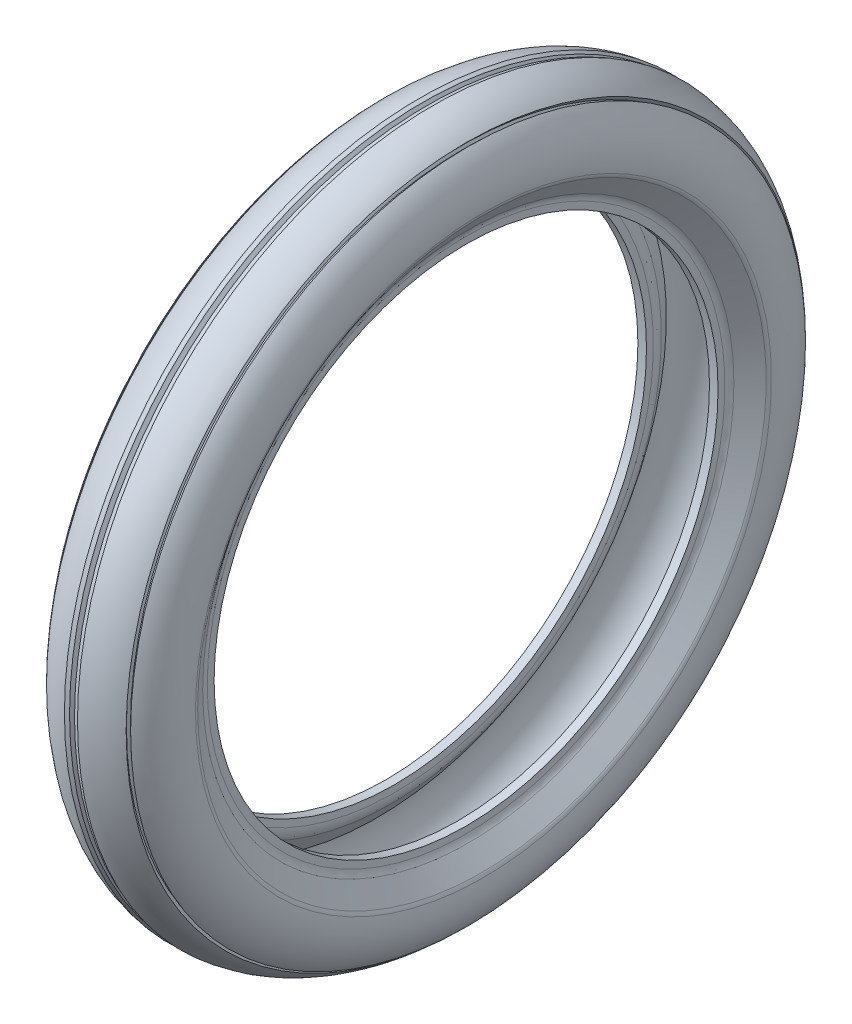
SolidWorks part; units mm, degrees
ref_plane "Front Plane" through (0, 0, 0) normal (0, 0, 1) x (1, 0, 0)
ref_plane "Top Plane" through (0, 0, 0) normal (0, 1, 0) x (1, 0, 0)
ref_plane "Right Plane" through (0, 0, 0) normal (1, 0, 0) x (0, 0, -1)
sketch "Sketch2" plane through (0, 0, 0) normal (0, 0, 1) x (1, 0, 0)
  line L0 (-71.6084, 0) -> (87.6813, 0) construction
  line L1 (0, 0) -> (0, 259.5059) construction
  line L2 (-35, 220) -> (-35, 226)
  line L3 (-36.9226, 231.8953) -> (-48.8214, 248.1984)
  line L4 (35, 220) -> (35, 226)
  line L5 (36.9226, 231.8953) -> (48.8214, 248.1984)
  line L6 (-27.5, 220) -> (-27.5, 226)
  line L7 (-30.8645, 236.3168) -> (-42.7633, 252.6199)
  line L8 (30.8645, 236.3168) -> (42.7633, 252.6199)
  line L9 (27.5, 220) -> (27.5, 226)
  line L10 (-27.5, 220) -> (-35, 220)
  line L11 (35, 220) -> (27.5, 220)
  line L12 (0, 343.7781) -> (0, 259.5059) construction
  line L16 (-5.6942, 310) -> (-2.6761, 308.5392)
  line L17 (-36.7306, 294.6191) -> (-32.5279, 290.6015)
  line L19 (-34.7713, 296.5603) -> (-31.3368, 292.9266)
  line L20 (34.7713, 296.5603) -> (31.3368, 292.9266)
  line L22 (36.7306, 294.6191) -> (32.5279, 290.6015)
  line L23 (-2.6761, 308.5392) -> (0, 304.4705)
  line L24 (0, 304.4705) -> (1.6662, 308.5392)
  line L25 (1.6662, 308.5392) -> (5.6942, 310)
  line L26 (-31.3368, 292.9266) -> (-32.5279, 290.6015)
  line L27 (32.5279, 290.6015) -> (31.3368, 292.9266)
  arc A0 (-50.1679, 251.4276) -> (-36.7306, 294.6191) centre (0, 259.5059) cw
  arc A1 (50.1679, 251.4276) -> (48.8214, 248.1984) centre (42.7633, 252.6199) cw
  arc A2 (-50.1679, 251.4276) -> (-48.8214, 248.1984) centre (-42.7633, 252.6199) ccw
  arc A3 (36.9226, 231.8953) -> (35, 226) centre (45, 226) ccw
  arc A4 (-36.9226, 231.8953) -> (-35, 226) centre (-45, 226) cw
  arc A5 (-30.8645, 236.3168) -> (-27.5, 226) centre (-45, 226) cw
  arc A6 (-42.7633, 252.6199) -> (-42.7633, 252.6199) centre (-42.7633, 252.6199) ccw
  arc A7 (-42.7633, 252.6199) -> (42.7633, 252.6199) centre (0, 259.5059) cw
  arc A8 (42.7633, 252.6199) -> (42.7633, 252.6199) centre (42.7633, 252.6199) cw
  arc A9 (30.8645, 236.3168) -> (27.5, 226) centre (45, 226) ccw
  arc A10 (5.6942, 310) -> (34.7713, 296.5603) centre (0, 259.5059) cw
  arc A11 (-50.1679, 251.4276) -> (50.1679, 251.4276) centre (0, 259.5059) cw construction
  arc A12 (-34.7713, 296.5603) -> (-5.6942, 310) centre (0, 259.5059) cw
  arc A13 (36.7306, 294.6191) -> (50.1679, 251.4276) centre (0, 259.5059) cw
  point P15 (49.8374, 249.5905)
  point P18 (-49.8374, 249.5905)
  point P21 (35, 229.2611)
  point P24 (-35, 229.2611)
  point P45 (0, 302)
  dimension "D8" = 70
  dimension "D3" = 220
  dimension "D2" = 310
  dimension "D1" = 7.5
revolve "Revolve2" add sketch "Sketch2" angle 360 about L0
